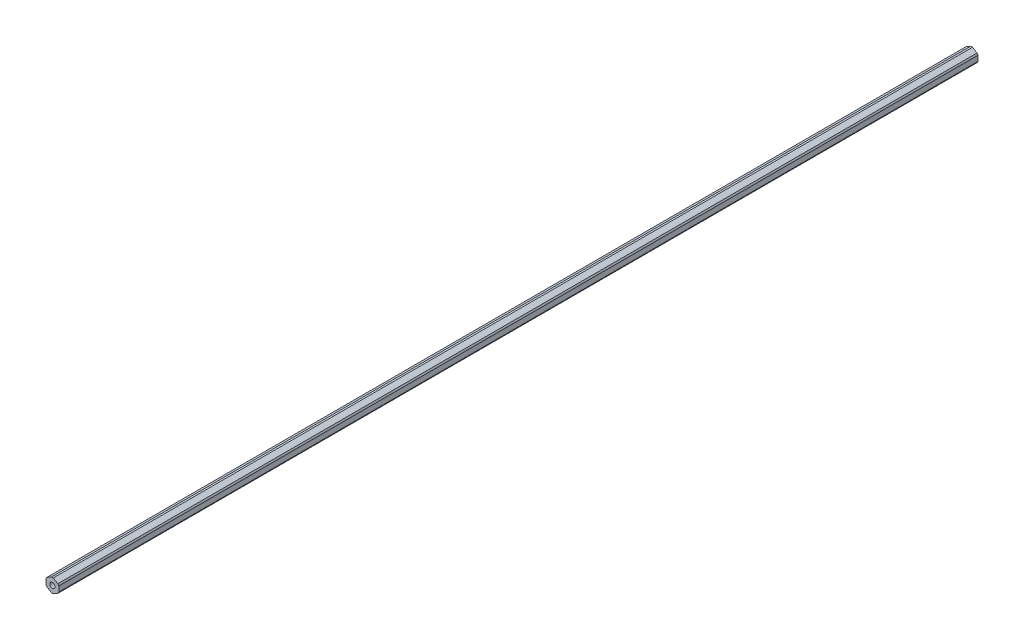
SolidWorks part; units mm, degrees
material "7075-T6 (SN)"
ref_plane "Front" through (0, 0, 0) normal (0, 0, 1) x (1, 0, 0)
ref_plane "Top" through (0, 0, 0) normal (0, 1, 0) x (1, 0, 0)
ref_plane "Right" through (0, 0, 0) normal (1, 0, 0) x (0, 0, -1)
sketch "Sketch1" plane through (0, 0, 0) normal (0, 0, 1) x (1, 0, 0)
  line L1 (0, 7.3323) -> (-6.35, 3.6662)
  line L2 (-6.35, 3.6662) -> (-6.35, -3.6662)
  line L3 (-6.35, -3.6662) -> (0, -7.3323)
  line L4 (0, -7.3323) -> (6.35, -3.6662)
  line L5 (6.35, -3.6662) -> (6.35, 3.6662)
  line L6 (6.35, 3.6662) -> (0, 7.3323)
  circle A0 centre (0, 0) radius 6.35 construction
  dimension "D1" = 12.7
extrude "Shaft Boss" add sketch "Sketch1" along normal blind 914.4
fillet "Fillet1" [suppressed] radius 0.508
sketch "Sketch2" plane through (0, 0, 0) normal (0, 0, -1) x (-1, 0, 0)
  circle A0 centre (0, 0) radius 6.877
  circle A1 centre (0, 0) radius 9.417
  dimension "D1" = 13.7541
  dimension "D2" = 2.54
extrude "Cut For Thunder Hex Round" cut sketch "Sketch2" against normal blind 914.4
sketch "Sketch3" plane through (0, 0, 0) normal (0, 0, -1) x (-1, 0, 0)
  circle A0 centre (0, 0) radius 2.5527
  dimension "D1" = 5.1054
extrude "Center Hole Cut" cut sketch "Sketch3" against normal blind 914.4
ref_plane "Plane1" through (0, 0, 914.4) normal (0, 0, 1) x (1, 0, 0)
ref_plane "Plane2" through (0, 0, 0) normal (0, 0, -1) x (-1, 0, 0)
other "SurfaceCut1"
equation "\"HS\"=1 / 2"
equation "\"L\"= 36"
equation "\"D1@Sketch1\"=\"HS\""
equation "\"D1@Shaft Boss\" = \"L\""
equation "\"THOD\"=.5415"
equation "\"Fillet1\"    = \"suppressed\""
equation "\"Shaft Boss\"= \"unsuppressed\""
equation "\"D1@Sketch2\"=\"THOD\""
equation "\"D1@Cut For Thunder Hex Round\" = \"L\""
equation "\"Cut For Thunder Hex Round\"  = \"unsuppressed\""
equation "\"THID\"=.201"
equation "\"D1@Sketch3\"=\"THID\""
equation "\"D1@Center Hole Cut\" = \"L\""
equation "\"Center Hole Cut\"   = \"unsuppressed\""
